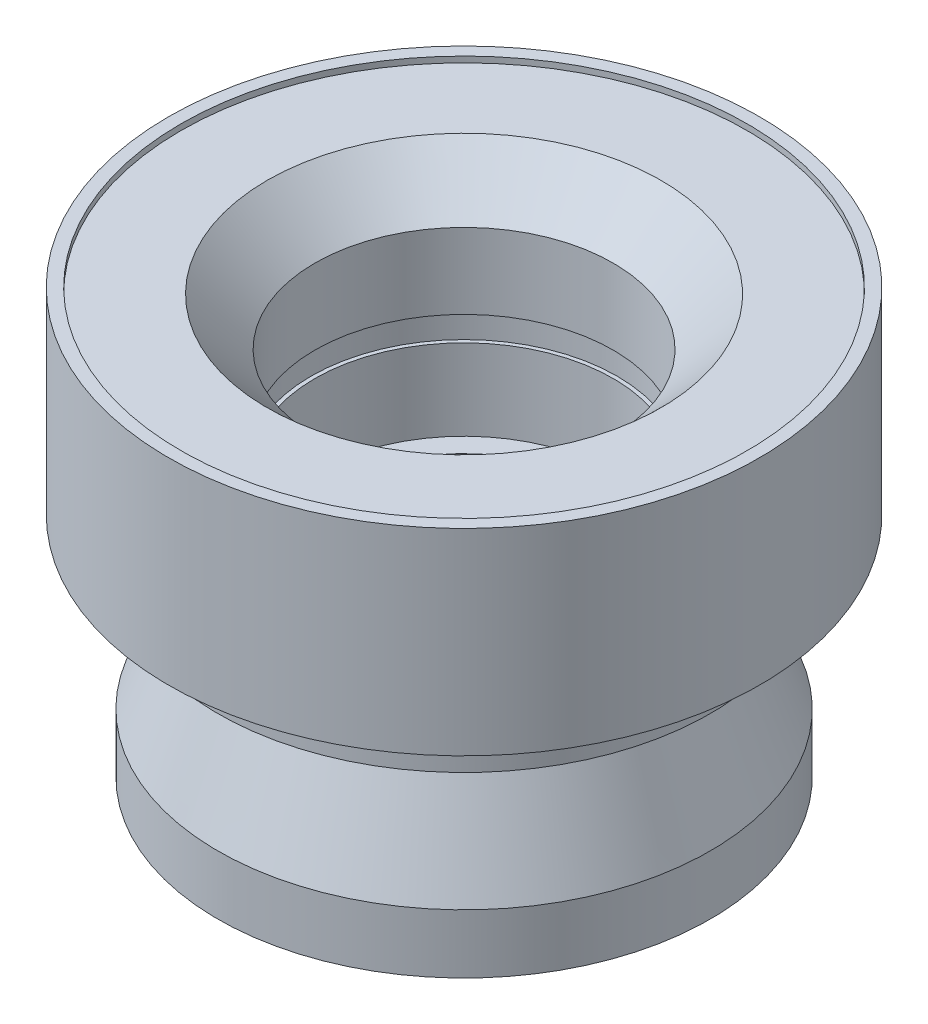
SolidWorks part; units mm, degrees
material "6061-T6 (SS)"
ref_plane "Front Plane" through (0, 0, 0) normal (0, 0, 1) x (1, 0, 0)
ref_plane "Top Plane" through (0, 0, 0) normal (0, 1, 0) x (1, 0, 0)
ref_plane "Right Plane" through (0, 0, 0) normal (1, 0, 0) x (0, 0, -1)
sketch "Sketch1" plane through (0, 0, 0) normal (0, 0, 1) x (1, 0, 0)
  line L0 (0, 41.94) -> (0, -22.3435) construction
  line L1 (12.7, 0) -> (12.7, 6.35) construction
  line L2 (12.7, 6.35) -> (25.4, 19.05) construction
  line L10 (38.1, 19.812) -> (38.1, -5.588)
  line L11 (38.1, -5.588) -> (31.75, -5.588)
  line L12 (31.75, -5.588) -> (31.75, -11.938)
  line L13 (31.75, -34.893) -> (25.4, -34.893)
  line L14 (25.4, -34.893) -> (12.7, 0) construction
  line L15 (36.5125, 19.812) -> (38.1, 19.812)
  line L16 (36.5125, 19.812) -> (36.5125, 19.05)
  line L17 (36.5125, 19.05) -> (25.4, 19.05)
  line L18 (25.4, -34.893) -> (27.8989, -51.6135) construction
  line L19 (31.75, -27.273) -> (26.1685, -11.938)
  line L20 (31.75, -11.938) -> (26.1685, -11.938)
  line L21 (31.75, -27.273) -> (31.75, -34.893)
  line L23 (19.2405, -10.433) -> (16.4973, -10.433)
  line L24 (19.2405, 12.8905) -> (25.4, 19.05)
  line L25 (16.4973, -10.433) -> (25.4, -34.893)
  line L26 (19.2405, 12.8905) -> (19.2405, 3.175)
  line L31 (19.2405, 0) -> (19.2405, -10.433)
  line L32 (19.2405, 3.175) -> (19.7485, 3.175)
  line L34 (19.2405, 0) -> (19.7485, 0)
  line L36 (19.7485, 3.175) -> (19.7485, 0)
  arc A1 (12.7, 0) -> (25.4, -34.893) centre (-66.7022, -48.6577) cw construction
  dimension "D12" = 8.5
  dimension "D1" = 12.7
  dimension "D2" = 76.2
  dimension "D3" = 73.025
  dimension "D4" = 45
  dimension "D5" = 63.5
  dimension "D6" = 25.4
  dimension "D7" = 6.35
  dimension "D8" = 20
  dimension "D9" = 50.8
  dimension "D10" = 0.762
  dimension "D11" = 50.8
  dimension "D13" = 6.35
  dimension "D14" = 7.62
  dimension "D15" = 38.481
  dimension "D16" = 2.7432
  dimension "D17" = 0.508
  dimension "D18" = 3.175
revolve "Revolve1" add sketch "Sketch1" angle 360 about L0
